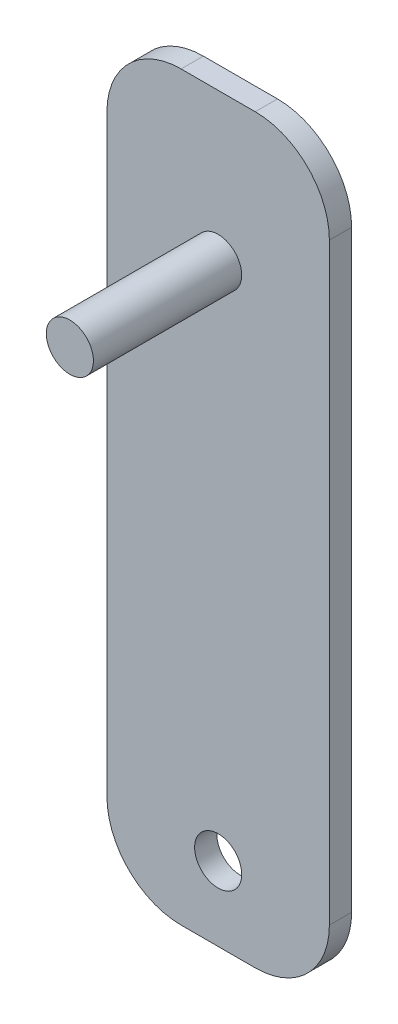
SolidWorks part; units mm, degrees
ref_plane "Alzado" through (0, 0, 0) normal (0, 0, 1) x (1, 0, 0)
ref_plane "Planta" through (0, 0, 0) normal (0, 1, 0) x (1, 0, 0)
ref_plane "Vista lateral" through (0, 0, 0) normal (1, 0, 0) x (0, 0, -1)
sketch "Croquis1" plane through (0, 0, 0) normal (0, 0, 1) x (1, 0, 0)
  line L0 (0, -40) -> (0, 30) construction
  line L1 (5, -50) -> (-5, -50)
  line L2 (15, -40) -> (15, 40)
  line L3 (5, 50) -> (-5, 50)
  line L4 (-15, -40) -> (-15, 40)
  line L5 (15, -50) -> (-15, 50) construction
  line L6 (15, 50) -> (-15, -50) construction
  circle A0 centre (0, -40) radius 3.175
  arc A1 (15, 40) -> (5, 50) centre (5, 40) ccw
  arc A2 (5, -50) -> (15, -40) centre (5, -40) ccw
  arc A3 (-5, -50) -> (-15, -40) centre (-5, -40) cw
  arc A4 (-5, 50) -> (-15, 40) centre (-5, 40) ccw
  point P0 (0, 0)
  dimension "D4" = 6.35
  dimension "D6" = 10
  dimension "D1" = 100
  dimension "D2" = 70
  dimension "D3" = 10
  dimension "D5" = 30
extrude "Saliente-Extruir1" add sketch "Croquis1" along normal blind 3
sketch "Croquis2" plane through (0, 0, 3) normal (0, 0, 1) x (1, 0, 0)
  line L0 (0, -40) -> (0, 30) construction
  circle A0 centre (0, 30) radius 3.175
  dimension "D2" = 6.35
  dimension "D1" = 70
extrude "Saliente-Extruir2" add sketch "Croquis2" along normal blind 20
